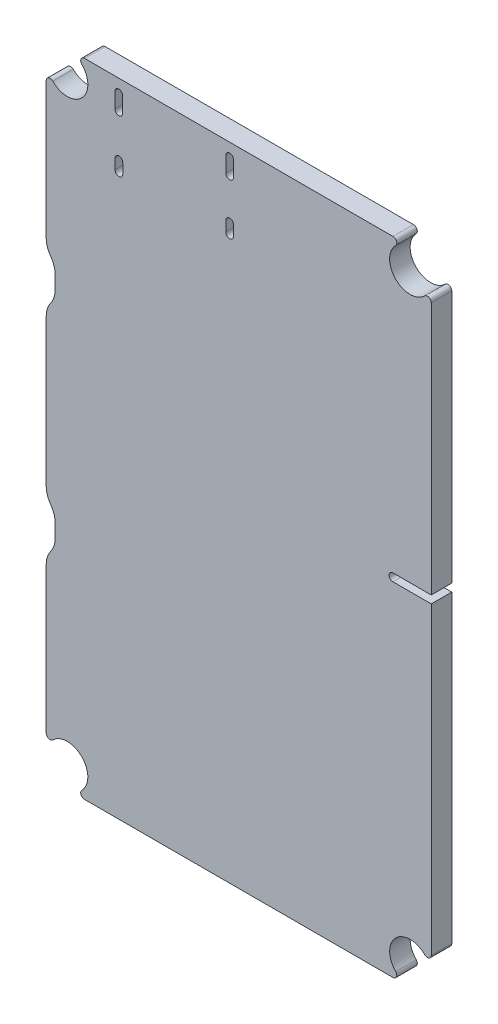
SolidWorks part; units mm, degrees
ref_plane "Front Plane" through (0, 0, 0) normal (0, 0, 1) x (1, 0, 0)
ref_plane "Top Plane" through (0, 0, 0) normal (0, 1, 0) x (1, 0, 0)
ref_plane "Right Plane" through (0, 0, 0) normal (1, 0, 0) x (0, 0, -1)
sketch "Sketch1" plane through (0, 0, 0) normal (0, 0, 1) x (1, 0, 0)
  line L28 (10, 12.987) -> (10, 24.35)
  line L29 (10.7, 26.5) -> (10.7, 27.5)
  line L30 (10, 29.65) -> (10, 41.1)
  line L31 (10.7, 43.25) -> (10.7, 44.25)
  line L32 (10, 46.4) -> (10, 57.013)
  line L33 (12.987, 60) -> (37.013, 60)
  line L34 (40, 57.013) -> (40, 12.987)
  line L35 (37.013, 10) -> (12.987, 10)
  arc A72 (10, 24.35) -> (10.35, 25.425) centre (11.8259, 24.35) cw
  arc A73 (10.35, 25.425) -> (10.7, 26.5) centre (8.8741, 26.5) ccw
  arc A74 (10.7, 27.5) -> (10.35, 28.575) centre (8.8741, 27.5) ccw
  arc A75 (10.35, 28.575) -> (10, 29.65) centre (11.8259, 29.65) cw
  arc A76 (10, 41.1) -> (10.35, 42.175) centre (11.8259, 41.1) cw
  arc A77 (10.35, 42.175) -> (10.7, 43.25) centre (8.8741, 43.25) ccw
  arc A78 (10.7, 44.25) -> (10.35, 45.325) centre (8.8741, 44.25) ccw
  arc A79 (10.35, 45.325) -> (10, 46.4) centre (11.8259, 46.4) cw
  arc A80 (10, 57.013) -> (10.5121, 57.2251) centre (10.3, 57.013) cw
  arc A81 (10.5121, 57.2251) -> (12.7749, 59.4879) centre (11.6449, 58.3551) ccw
  arc A82 (12.7749, 59.4879) -> (12.987, 60) centre (12.987, 59.7) cw
  arc A83 (37.013, 60) -> (37.2251, 59.4879) centre (37.013, 59.7) cw
  arc A84 (37.2251, 59.4879) -> (39.4879, 57.2251) centre (38.3551, 58.3551) ccw
  arc A85 (39.4879, 57.2251) -> (40, 57.013) centre (39.7, 57.013) cw
  arc A86 (40, 12.987) -> (39.4879, 12.7749) centre (39.7, 12.987) cw
  arc A87 (39.4879, 12.7749) -> (37.2251, 10.5121) centre (38.3579, 11.6421) ccw
  arc A88 (37.2251, 10.5121) -> (37.013, 10) centre (37.013, 10.3) cw
  arc A89 (12.987, 10) -> (12.7749, 10.5121) centre (12.987, 10.3) cw
  arc A90 (12.7749, 10.5121) -> (10.5121, 12.7749) centre (11.6421, 11.6421) ccw
  arc A91 (10.5121, 12.7749) -> (10, 12.987) centre (10.3, 12.987) cw
extrude "Board" add sketch "Sketch1" along normal blind 1.5994
sketch "Sketch2" plane through (0, 0, 1.5994) normal (0, 0, 1) x (1, 0, 0)
  line L0 (15.656, 58.964) -> (15.656, 57.764) construction
  line L1 (15.956, 58.964) -> (15.956, 57.764)
  line L2 (15.356, 58.964) -> (15.356, 57.764)
  line L3 (15.6645, 54.4652) -> (15.6645, 53.6652) construction
  line L4 (15.9645, 54.4652) -> (15.9645, 53.6652)
  line L5 (15.3645, 54.4652) -> (15.3645, 53.6652)
  line L6 (24.292, 54.584) -> (24.292, 53.784) construction
  line L7 (24.592, 54.584) -> (24.592, 53.784)
  line L8 (23.992, 54.584) -> (23.992, 53.784)
  line L9 (24.292, 58.964) -> (24.292, 57.764) construction
  line L10 (24.592, 58.964) -> (24.592, 57.764)
  line L11 (23.992, 58.964) -> (23.992, 57.764)
  arc A0 (15.956, 58.964) -> (15.356, 58.964) centre (15.656, 58.964) ccw
  arc A1 (15.356, 57.764) -> (15.956, 57.764) centre (15.656, 57.764) ccw
  arc A2 (15.9645, 54.4652) -> (15.3645, 54.4652) centre (15.6645, 54.4652) ccw
  arc A3 (15.3645, 53.6652) -> (15.9645, 53.6652) centre (15.6645, 53.6652) ccw
  arc A4 (24.592, 54.584) -> (23.992, 54.584) centre (24.292, 54.584) ccw
  arc A5 (23.992, 53.784) -> (24.592, 53.784) centre (24.292, 53.784) ccw
  arc A6 (24.592, 58.964) -> (23.992, 58.964) centre (24.292, 58.964) ccw
  arc A7 (23.992, 57.764) -> (24.592, 57.764) centre (24.292, 57.764) ccw
  point P2 (15.656, 58.364)
  point P8 (15.6645, 54.0652)
  point P15 (24.292, 54.184)
  point P22 (24.292, 58.364)
extrude "Cut-Extrude1" cut sketch "Sketch2" against normal through all
sketch "Sketch3" plane through (0, 0, 1.5994) normal (0, 0, 1) x (1, 0, 0)
  line L0 (37.015, 37.3) -> (41.715, 37.3)
  line L1 (41.715, 37.3) -> (41.715, 36.7)
  line L2 (41.715, 36.7) -> (37.015, 36.7)
  arc A0 (37.015, 36.7) -> (37.015, 37.3) centre (37.015, 37) cw
extrude "Cut-Extrude2" cut sketch "Sketch3" against normal through all
